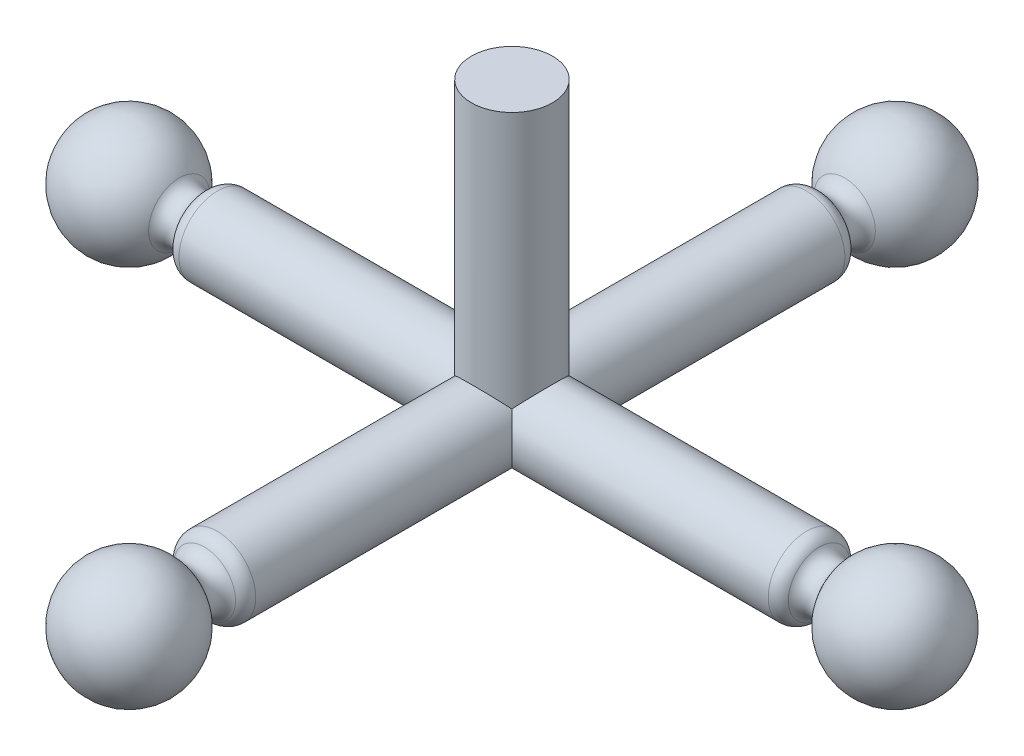
SolidWorks part; units mm, degrees
ref_plane "Front Plane" through (0, 0, 0) normal (0, 0, 1) x (1, 0, 0)
ref_plane "Top Plane" through (0, 0, 0) normal (0, 1, 0) x (1, 0, 0)
ref_plane "Right Plane" through (0, 0, 0) normal (1, 0, 0) x (0, 0, -1)
sketch "Sketch1" plane through (0, 0, 0) normal (0, 0, 1) x (1, 0, 0)
  line L0 (30, 0) -> (-30, 0)
  line L1 (-20, 2.6047) -> (20, 2.6047)
  line L2 (0, 0) -> (0, 2.6047) construction
  arc A0 (-30, 0) -> (-22.5856, 2.0838) centre (-26, 0) cw
  arc A1 (-22.5856, 2.0838) -> (-20.866, 2.1047) centre (-21.7321, 2.6047) ccw
  arc A2 (-20.866, 2.1047) -> (-20, 2.6047) centre (-20, 1.6047) cw
  arc A3 (20.866, 2.1047) -> (20, 2.6047) centre (20, 1.6047) ccw
  arc A4 (22.5856, 2.0838) -> (20.866, 2.1047) centre (21.7321, 2.6047) cw
  arc A5 (30, 0) -> (22.5856, 2.0838) centre (26, 0) ccw
  dimension "D3" = 4
  dimension "D4" = 1
  dimension "D1" = 30
  dimension "D2" = 20
revolve "Revolve1" add sketch "Sketch1" angle 360 about L0
sketch "Sketch2" plane through (0, 0, 0) normal (1, 0, 0) x (0, 0, -1)
  line L0 (0, 0) -> (-30, 0)
  line L1 (-19.9971, 2.6) -> (0.0029, 2.6)
  line L3 (20.0029, 2.6) -> (0.0029, 2.6)
  line L4 (0, 0) -> (30, 0)
  arc A0 (-30, 0) -> (-22.5833, 2.08) centre (-26, 0) cw
  arc A1 (-22.5833, 2.08) -> (-20.8631, 2.1) centre (-21.7292, 2.6) ccw
  arc A2 (-20.8631, 2.1) -> (-19.9971, 2.6) centre (-19.9971, 1.6) cw
  arc A3 (20.8675, 2.1024) -> (20.0029, 2.6) centre (20.0029, 1.6) ccw
  arc A4 (22.5857, 2.0839) -> (20.8675, 2.1024) centre (21.7321, 2.6048) cw
  arc A5 (30, 0) -> (22.5857, 2.0839) centre (26, 0) ccw
  point P17 (26.1592, -0.3491)
  dimension "D3" = 4
  dimension "D4" = 1
  dimension "D8" = 4
  dimension "D9" = 1
  dimension "D1" = 30
  dimension "D2" = 20
  dimension "D5" = 2.6
  dimension "D6" = 30
  dimension "D7" = 20
revolve "Revolve4" add sketch "Sketch2" angle 360 about L0
sketch "Sketch3" plane through (0, 0, 0) normal (0, 0, 1) x (1, 0, 0)
  line L0 (0, 0) -> (-2.75, 0)
  line L1 (-2.75, 0) -> (-2.75, 19.1628)
  line L2 (-2.75, 19.1628) -> (0, 19.1628)
  line L3 (0, 19.1628) -> (0, 0)
  dimension "D1" = 2.75
revolve "Revolve5" add sketch "Sketch3" angle 360 about L3
